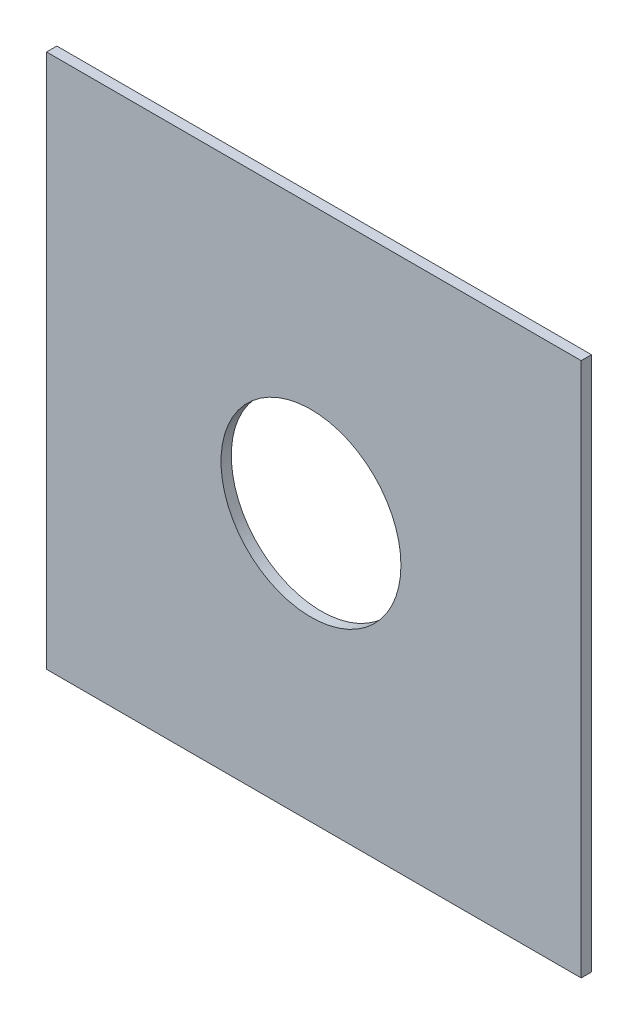
SolidWorks part; units mm, degrees
ref_plane "Front Plane" through (0, 0, 0) normal (0, 0, 1) x (1, 0, 0)
ref_plane "Top Plane" through (0, 0, 0) normal (0, 1, 0) x (1, 0, 0)
ref_plane "Right Plane" through (0, 0, 0) normal (1, 0, 0) x (0, 0, -1)
sketch "Sketch1" plane through (0, 0, 0) normal (0, 0, 1) x (1, 0, 0)
  line L1 (-257.1859, 260) -> (262.8141, 260)
  line L2 (-257.1859, 260) -> (-257.1859, -260)
  line L3 (-257.1859, -260) -> (262.8141, -260)
  line L4 (262.8141, 260) -> (262.8141, -260)
  circle A1 centre (0, 0) radius 87.5
  dimension "D8" = 175
  dimension "D1" = 520
  dimension "D2" = 520
  dimension "D3" = 260
extrude "Boss-Extrude1" add sketch "Sketch1" along normal blind 10
